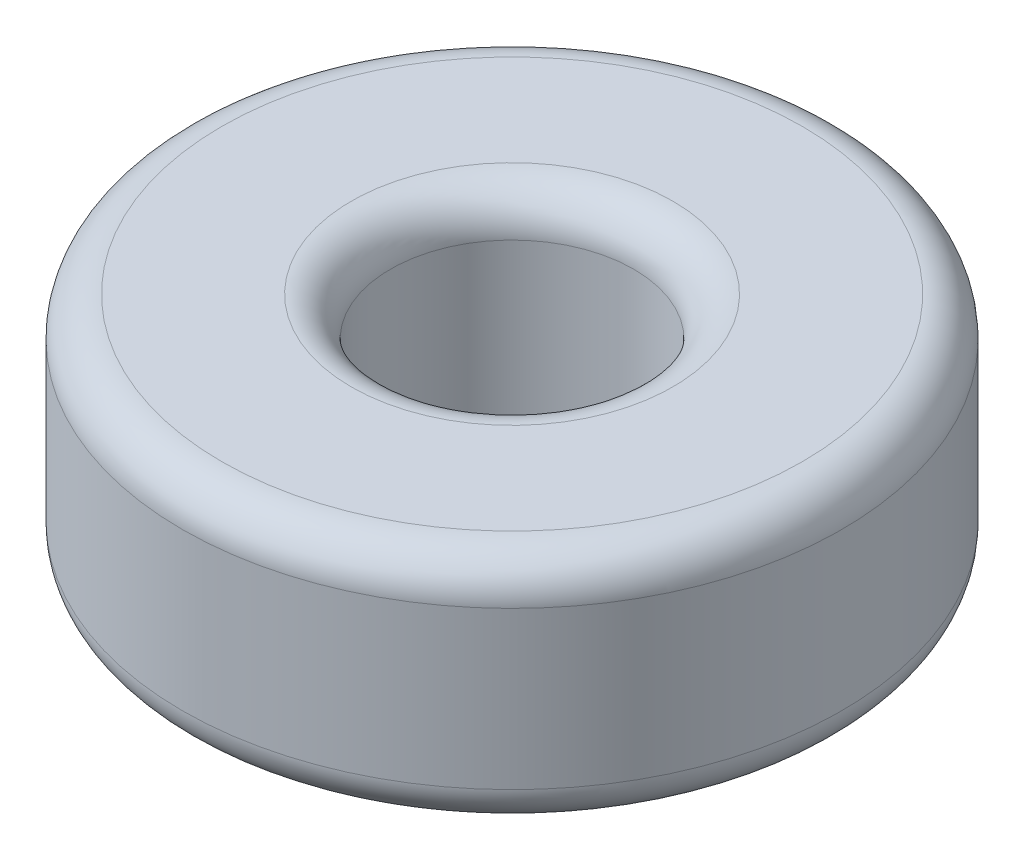
SolidWorks part; units mm, degrees
ref_plane "Front Plane" through (0, 0, 0) normal (0, 0, 1) x (1, 0, 0)
ref_plane "Top Plane" through (0, 0, 0) normal (0, 1, 0) x (1, 0, 0)
ref_plane "Right Plane" through (0, 0, 0) normal (1, 0, 0) x (0, 0, -1)
sketch "Sketch1" plane through (0, 0, 0) normal (0, 1, 0) x (1, 0, 0)
  circle A0 centre (0, 0) radius 3.1
  circle A1 centre (0, 0) radius 8.4
  dimension "D1" = 6.2
  dimension "D2" = 16.8
extrude "Boss-Extrude1" add sketch "Sketch1" along normal blind 6
fillet "Fillet1" radius 1 4 edges at (0, 0, 3.1) (0, 0, 8.4) (0, 6, 3.1) (0, 6, 8.4)
